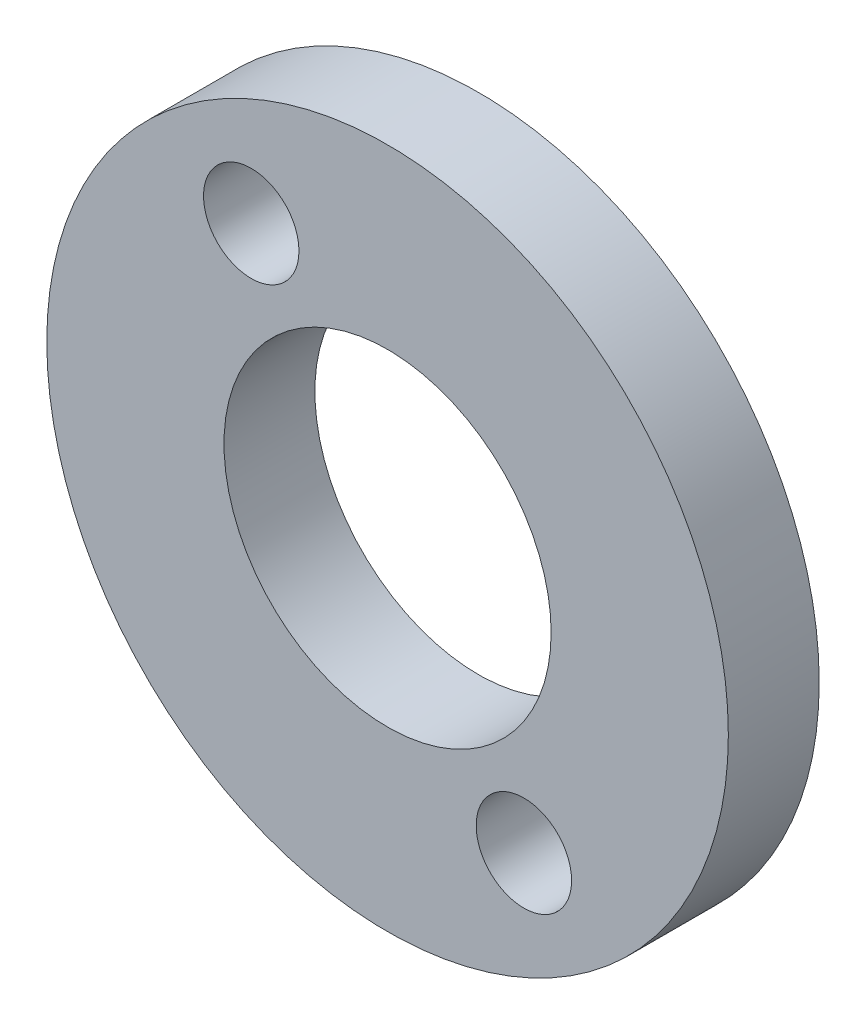
SolidWorks part; units mm, degrees
ref_plane "Plan de face" through (0, 0, 0) normal (0, 0, 1) x (1, 0, 0)
ref_plane "Plan de dessus" through (0, 0, 0) normal (0, 1, 0) x (1, 0, 0)
ref_plane "Plan de droite" through (0, 0, 0) normal (1, 0, 0) x (0, 0, -1)
sketch "Esquisse2" plane through (0, 0, 0) normal (0, 0, 1) x (1, 0, 0)
  line L0 (0, 10.6138) -> (0, -15.3486) construction
  line L1 (-15.9092, 0) -> (31.0419, 0) construction
  circle A0 centre (0, 0) radius 7.5
  circle A1 centre (-3, 4.5) radius 1.05
  circle A2 centre (3, -4.5) radius 1.05
  circle A3 centre (0, 0) radius 3.6
  dimension "D1" = 15
  dimension "D2" = 3
  dimension "D6" = 2.1
  dimension "D7" = 7.2
  dimension "D3" = 3
  dimension "D4" = 4.5
  dimension "D5" = 4.5
extrude "Boss.-Extru.1" add sketch "Esquisse2" along normal blind 2
